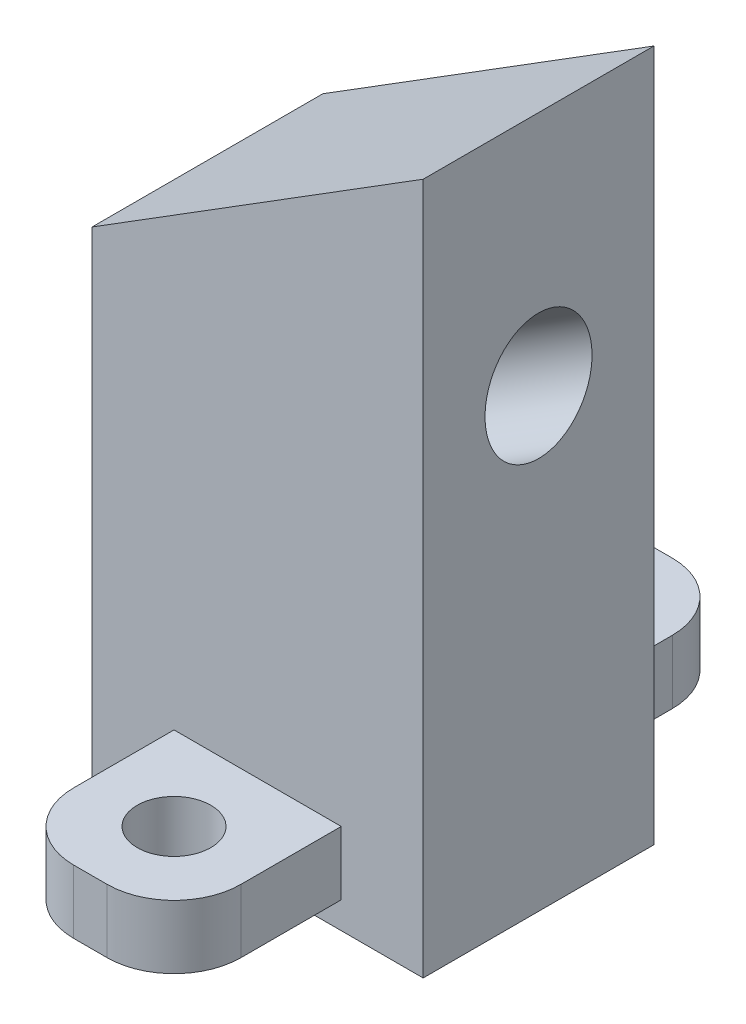
SolidWorks part; units mm, degrees
ref_plane "前视基准面" through (0, 0, 0) normal (0, 0, 1) x (1, 0, 0)
ref_plane "上视基准面" through (0, 0, 0) normal (0, 1, 0) x (1, 0, 0)
ref_plane "右视基准面" through (0, 0, 0) normal (1, 0, 0) x (0, 0, -1)
sketch "草图2" plane through (0, 0, 0) normal (0, 1, 0) x (1, 0, 0)
  line L1 (-4.95, 3.45) -> (7.45, 3.45)
  line L2 (-7.45, 0.95) -> (-7.45, -0.95)
  line L3 (-4.95, -3.45) -> (7.45, -3.45)
  line L4 (7.45, 3.45) -> (7.45, -3.45)
  line L5 (-7.45, 3.45) -> (7.45, -3.45) construction
  line L6 (-7.45, -3.45) -> (7.45, 3.45) construction
  arc A0 (-4.95, -3.45) -> (-7.45, -0.95) centre (-4.95, -0.95) cw
  arc A1 (-4.95, 3.45) -> (-7.45, 0.95) centre (-4.95, 0.95) ccw
  point P0 (0, 0)
  dimension "D3" = 2.5
  dimension "D1" = 6.9
  dimension "D2" = 14.9
extrude "凸台-拉伸1" add sketch "草图2" along normal blind 1.5
sketch "草图3" plane through (0, 1.5, 0) normal (0, 1, 0) x (1, 0, 0)
  line L0 (-7.45, 0) -> (-4.95, 0) construction
  line L1 (-7.45, 0.95) -> (-7.45, -0.95) construction
  circle A0 centre (-4.95, 0) radius 1.1
  dimension "D2" = 2.2
  dimension "D1" = 2.5
extrude "切除-拉伸1" cut sketch "草图3" against normal blind 5
sketch "草图5" plane through (0, 0, -3.45) normal (0, 0, -1) x (-1, 0, 0)
  line L0 (2.45, 1.5) -> (2.45, 14.5)
  line L2 (2.45, 14.5) -> (-7.45, 20.6862)
  line L3 (-7.45, 20.6862) -> (-7.45, 1.5)
  line L4 (-7.45, 1.5) -> (2.45, 1.5)
  line L5 (2.45, 14.5) -> (-2.1321, 14.5) construction
  line L7 (3.85, 1.5) -> (3.85, 0) construction
  dimension "D1" = 32
  dimension "D2" = 13
  dimension "D3" = 1.4
extrude "凸台-拉伸2" add sketch "草图5" against normal blind 6.9
sketch "草图7" plane through (0, 0, 0) normal (0, 0, 1) x (1, 0, 0)
  line L0 (-6.2038, 5.0793) -> (11.6269, 16.2211)
  line L2 (-2.45, 14.5) -> (7.45, 20.6862) construction
  dimension "D1" = 6
sweep "切除-扫描1" cut path "草图7" circular profile diameter 3.2 parameters "D3"=3.2
sketch "草图80" plane through (0, 1.5, 0) normal (0, 1, 0) x (1, 0, 0)
  line L4 (-4.95, -3.45) -> (-2.45, -3.45)
  line L5 (-2.45, -3.45) -> (-2.45, 3.45)
  line L6 (-2.45, 3.45) -> (-4.95, 3.45)
  line L7 (-7.45, 0.95) -> (-7.45, -0.95)
  line L8 (-4.95, -3.45) -> (-2.45, -3.45)
  line L9 (-2.45, -3.45) -> (-2.45, 3.45)
  line L10 (-2.45, 3.45) -> (-4.95, 3.45)
  line L11 (-7.45, 0.95) -> (-7.45, -0.95)
  arc A2 (-4.95, 3.45) -> (-7.45, 0.95) centre (-4.95, 0.95) ccw
  arc A3 (-7.45, -0.95) -> (-4.95, -3.45) centre (-4.95, -0.95) ccw
  arc A4 (-4.95, 3.45) -> (-7.45, 0.95) centre (-4.95, 0.95) ccw
  arc A5 (-7.45, -0.95) -> (-4.95, -3.45) centre (-4.95, -0.95) ccw
  dimension "D1" = 0
extrude "切除-拉伸5" cut sketch "草图80" against normal blind 7.8
sketch "草图81" plane through (0, 0, 0) normal (0, -1, 0) x (1, 0, 0)
  line L0 (2.5, -3.45) -> (2.5, 3.45) construction
  line L1 (7.45, -3.45) -> (-2.45, -3.45) construction
  line L2 (-2.45, 3.45) -> (7.45, 3.45) construction
  line L3 (2.5, 3.45) -> (2.5, 5.95) construction
  line L4 (0, 8.45) -> (5, 8.45)
  line L5 (0, 8.45) -> (0, -1.55)
  line L6 (0, -1.55) -> (5, -1.55)
  line L7 (5, 8.45) -> (5, -1.55)
  line L8 (0, 8.45) -> (5, -1.55) construction
  line L9 (0, -1.55) -> (5, 8.45) construction
  line L10 (0, 3.45) -> (5, 3.45)
  circle A0 centre (2.5, 5.95) radius 1.1
  line M7 (7.45, 3.45) -> (-2.45, 3.45)
  dimension "D3" = 2.2
  dimension "D1" = 5
  dimension "D2" = 5
  dimension "D4" = 2.5
extrude "凸台-拉伸8" add sketch "草图81" against normal blind 1.9 from offset 0.8 contours L7 L4 L5 A0 M7 offset against normal yes
fillet "圆角1" radius 2 2 edges at (0, 1.75, 8.45) (5, 1.75, 8.45)
ref_plane "基准面2" through (0, 0, 0) normal (0, 0, 1) x (1, 0, 0)
mirror "镜向1" about plane through (0, 0, 0) normal (0, 0, 1) of "凸台-拉伸8", "圆角1"
sketch "草图83" plane through (-2.45, 0, 0) normal (-1, 0, 0) x (0, 0, 1)
  line L4 (-3.45, 14.5) -> (-3.45, 0)
  line L5 (-3.45, 0) -> (3.45, 0)
  line L6 (3.45, 0) -> (3.45, 14.5)
  line L7 (3.45, 14.5) -> (-3.45, 14.5)
  line L8 (-3.45, 14.5) -> (-3.45, 0)
  line L9 (-3.45, 0) -> (3.45, 0)
  line L10 (3.45, 0) -> (3.45, 14.5)
  line L11 (3.45, 14.5) -> (-3.45, 14.5)
  dimension "D1" = 0
extrude "凸台-拉伸10" add sketch "草图83" against normal blind 1
